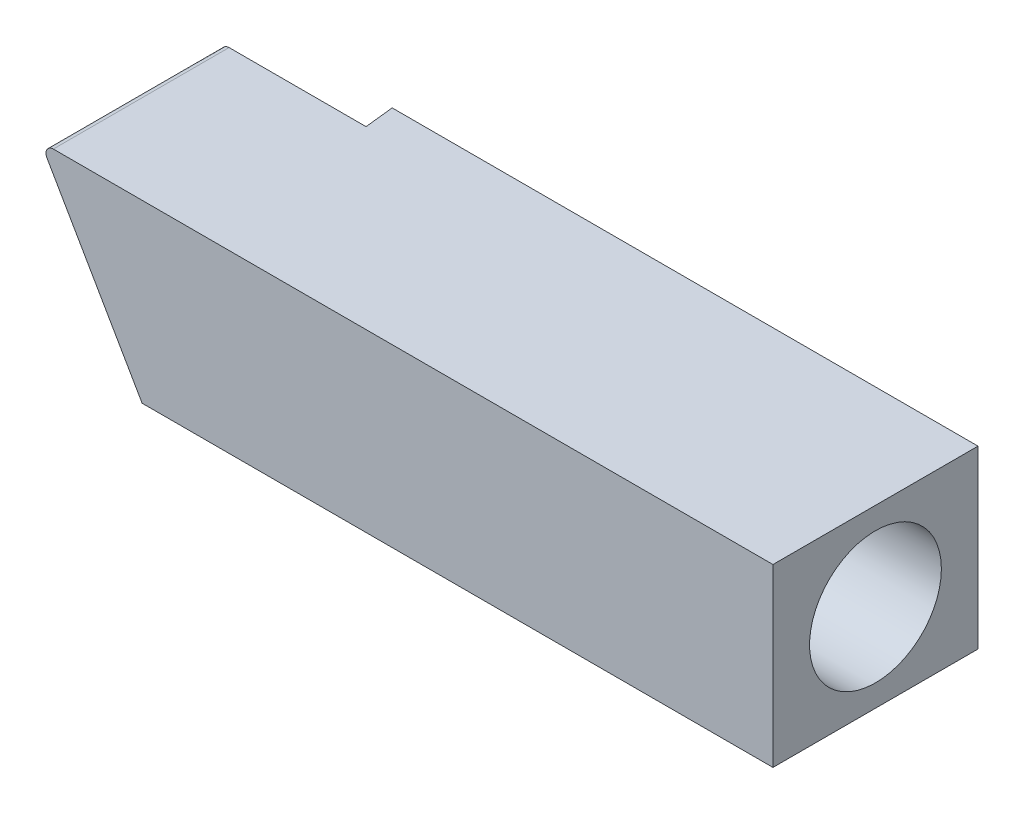
SolidWorks part; units mm, degrees
ref_plane "Front" through (0, 0, 0) normal (0, 0, 1) x (1, 0, 0)
ref_plane "Top" through (0, 0, 0) normal (0, 1, 0) x (1, 0, 0)
ref_plane "Right" through (0, 0, 0) normal (1, 0, 0) x (0, 0, -1)
sketch "Sketch1" plane through (0, 0, 0) normal (0, 0, 1) x (1, 0, 0)
  line L0 (-22.6463, 12) -> (27.3537, 12)
  line L1 (-22.6463, 12) -> (-15.7181, 0)
  line L2 (-15.7181, 0) -> (27.3537, 0)
  line L3 (27.3537, 12) -> (27.3537, 0)
  dimension "D1" = 50
  dimension "D2" = 60
  dimension "D3" = 12
extrude "Extrude1" add sketch "Sketch1" along normal blind 14
sketch "Sketch2" plane through (0, 12, 0) normal (0, 1, 0) x (1, 0, 0)
  line L0 (-22.6463, -2) -> (-12.4275, -2)
  line L2 (-12.6463, 0) -> (-12.4275, -2)
  line L4 (27.3537, 0) -> (-22.6463, 0)
  line L5 (-22.6463, 0) -> (-22.6463, -14)
  line L6 (-22.6463, -14) -> (27.3537, -14)
  line L7 (27.3537, -14) -> (27.3537, 0)
  line L8 (-12.6463, 0) -> (-22.6463, 0)
  line L9 (-22.6463, 0) -> (-22.6463, -2)
  dimension "D2" = 10
  dimension "D3" = 2
  dimension "D1" = 0
extrude "Cut-Extrude1" cut sketch "Sketch2" against normal blind 14
fillet "Fillet1" radius 0.5 1 edges at (-22.6463, 12, 8)
sketch "Sketch3" plane through (27.3537, 0, 0) normal (1, 0, 0) x (0, 0, -1)
  line L0 (-7, 12) -> (-7, 0) construction
  line L1 (-14, 6) -> (0, 6) construction
  circle A0 centre (-7, 6) radius 4.5
extrude "Cut-Extrude2" cut sketch "Sketch3" against normal blind 25
